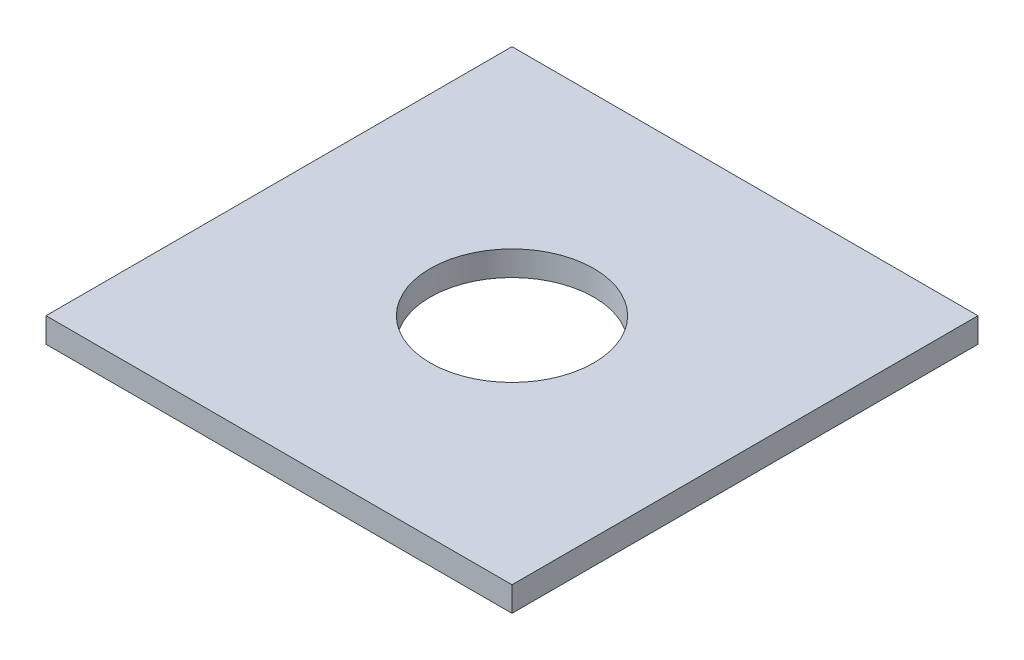
SolidWorks part; units mm, degrees
material "1.0553 (S355J0)"
ref_plane "Front Plane" through (0, 0, 0) normal (0, 0, 1) x (1, 0, 0)
ref_plane "Top Plane" through (0, 0, 0) normal (0, 1, 0) x (1, 0, 0)
ref_plane "Right Plane" through (0, 0, 0) normal (1, 0, 0) x (0, 0, -1)
sketch "Sketch1" plane through (0, 0, 0) normal (0, 1, 0) x (1, 0, 0)
  line L1 (-47, -47) -> (47, -47)
  line L2 (-47, -47) -> (-47, 47)
  line L3 (-47, 47) -> (47, 47)
  line L4 (47, -47) -> (47, 47)
  line L5 (-47, -47) -> (47, 47) construction
  line L6 (-47, 47) -> (47, -47) construction
  point P0 (0, 0)
  dimension "D1" = 94
  dimension "D2" = 94
extrude "Boss-Extrude1" add sketch "Sketch1" along normal blind 5
sketch "Sketch2" plane through (0, 5, 0) normal (0, 1, 0) x (1, 0, 0)
  circle A0 centre (0, 0) radius 16.5
  dimension "D1" = 33
extrude "Cut-Extrude1" cut sketch "Sketch2" against normal up to next
